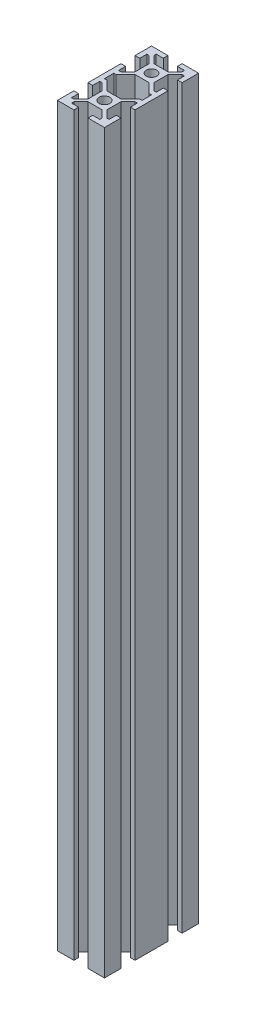
SolidWorks part; units mm, degrees
ref_plane "Front Plane" through (0, 0, 0) normal (0, 0, 1) x (1, 0, 0)
ref_plane "Top Plane" through (0, 0, 0) normal (0, 1, 0) x (1, 0, 0)
ref_plane "Right Plane" through (0, 0, 0) normal (1, 0, 0) x (0, 0, -1)
sketch "Sketch1" plane through (0, 0, 0) normal (0, 1, 0) x (1, 0, 0)
  line L0 (10, 6.326) -> (10, -39.1326) construction
  line L4 (20, 0) -> (20, -7)
  line L5 (-2.6965, -10) -> (22.6965, -10) construction
  line L6 (-2.6965, -30) -> (22.6965, -30) construction
  line L7 (2, -4) -> (2, -7)
  line L9 (18, -4) -> (18, -7)
  line L10 (4, -2) -> (7, -2)
  line L11 (7, 0) -> (7, -2)
  line L12 (7, -6) -> (13, -6)
  line L13 (6, -7) -> (6, -13)
  line L14 (7, -14) -> (13, -14)
  line L15 (14, -7) -> (14, -13)
  line L16 (6, -6) -> (14, -14) construction
  line L17 (6, -14) -> (14, -6) construction
  line L18 (7, -26) -> (13, -26)
  line L19 (6, -27) -> (6, -33)
  line L20 (7, -34) -> (13, -34)
  line L21 (14, -27) -> (14, -33)
  line L22 (6, -26) -> (14, -34) construction
  line L23 (6, -34) -> (14, -26) construction
  line L24 (13, 0) -> (13, -2)
  line L25 (13, 0) -> (20, 0)
  line L26 (13, -2) -> (16, -2)
  line L27 (0, 0) -> (20, 0) construction
  line L28 (0, -7) -> (2, -7)
  line L29 (2, -2) -> (18, -2) construction
  line L30 (18, -7) -> (20, -7)
  line L31 (6, -7) -> (3, -4)
  line L32 (14, -7) -> (17, -4)
  line L33 (13, -6) -> (16, -3)
  line L34 (18, -2) -> (18, -38) construction
  line L35 (7, -6) -> (4, -3)
  line L36 (23.1857, -20) -> (-3.1857, -20) construction
  line L37 (2, -2) -> (2, -38) construction
  line L38 (14, -13) -> (17, -16)
  line L39 (13, -14) -> (17, -18)
  line L40 (7, -14) -> (3, -18)
  line L41 (6, -13) -> (3, -16)
  line L42 (3, -18) -> (2, -18)
  line L43 (17, -18) -> (18, -18)
  line L44 (2, -18) -> (2, -22)
  line L45 (18, -18) -> (18, -22)
  line L46 (0, -13) -> (2, -13)
  line L47 (18, -13) -> (20, -13)
  line L48 (0, -13) -> (0, -27)
  line L49 (2, -13) -> (2, -16)
  line L50 (0, 0) -> (0, -40) construction
  line L51 (18, -13) -> (18, -16)
  line L52 (20, -13) -> (20, -27)
  line L53 (2, -16) -> (3, -16)
  line L54 (20, 0) -> (20, -40) construction
  line L55 (18, -16) -> (17, -16)
  line L56 (0, 0) -> (7, 0)
  line L59 (2, -4) -> (3, -4)
  line L60 (4, -2) -> (4, -3)
  line L61 (0, 0) -> (0, -7)
  line L62 (18, -4) -> (17, -4)
  line L63 (16, -2) -> (16, -3)
  line L66 (7, -26) -> (3, -22)
  line L67 (2, -38) -> (18, -38) construction
  line L68 (0, -40) -> (20, -40) construction
  line L69 (13, -26) -> (17, -22)
  line L70 (17, -22) -> (18, -22)
  line L71 (2, -24) -> (2, -27)
  line L72 (18, -27) -> (20, -27)
  line L73 (18, -27) -> (18, -24)
  line L74 (18, -24) -> (17, -24)
  line L75 (14, -27) -> (17, -24)
  line L76 (14, -33) -> (17, -36)
  line L77 (18, -36) -> (17, -36)
  line L78 (18, -36) -> (18, -33)
  line L79 (18, -33) -> (20, -33)
  line L80 (20, -40) -> (20, -33)
  line L81 (13, -40) -> (20, -40)
  line L82 (13, -40) -> (13, -38)
  line L83 (13, -38) -> (16, -38)
  line L84 (16, -38) -> (16, -37)
  line L85 (13, -34) -> (16, -37)
  line L86 (7, -34) -> (4, -37)
  line L87 (4, -38) -> (4, -37)
  line L88 (4, -38) -> (7, -38)
  line L89 (7, -40) -> (7, -38)
  line L90 (0, -40) -> (7, -40)
  line L91 (0, -40) -> (0, -33)
  line L92 (0, -33) -> (2, -33)
  line L93 (2, -36) -> (2, -33)
  line L94 (2, -36) -> (3, -36)
  line L95 (6, -33) -> (3, -36)
  line L96 (6, -27) -> (3, -24)
  line L97 (2, -24) -> (3, -24)
  line L98 (2, -27) -> (2, -24)
  line L99 (0, -27) -> (2, -27)
  line L100 (3, -22) -> (2, -22)
  line L101 (18, -24) -> (18, -27)
  circle A0 centre (10, -10) radius 2.2132
  circle A1 centre (10, -30) radius 2.2889
  point P10 (10, -10)
  point P13 (10, -30)
  point P38 (18.5, -2.5)
  point P40 (17.5, -1.5)
  point P50 (10, -20)
  dimension "D1" = 20
  dimension "D6" = 8
  dimension "D7" = 8
  dimension "D8" = 8
  dimension "D9" = 8
  dimension "D11" = 7
  dimension "D13" = 7
  dimension "D16" = 1
  dimension "D17" = 1
  dimension "D18" = 6
  dimension "D19" = 6
  dimension "D20" = 1
  dimension "D3" = 7
  dimension "D5" = 2
extrude "Boss-Extrude1" add sketch "Sketch1" along normal blind 313 contours L48 L99 L71 L97 L96 L19 L95 L94 L93 L92 L91 L90 L89 L88 L87 L86 L20 L85 L84 L83 L82 L81 L80 L79 L78 L77 L76 L21 L75 L74 L73 L72 L52 L47 L51 L55 L38 L15 L32 L62 L9 L30 L4 L25 L24 L26 L63 L33 L12 L35 L60
equation "\"D7@Sketch1\"=\"D6@Sketch1\""
equation "\"D9@Sketch1\"=\"D8@Sketch1\""
